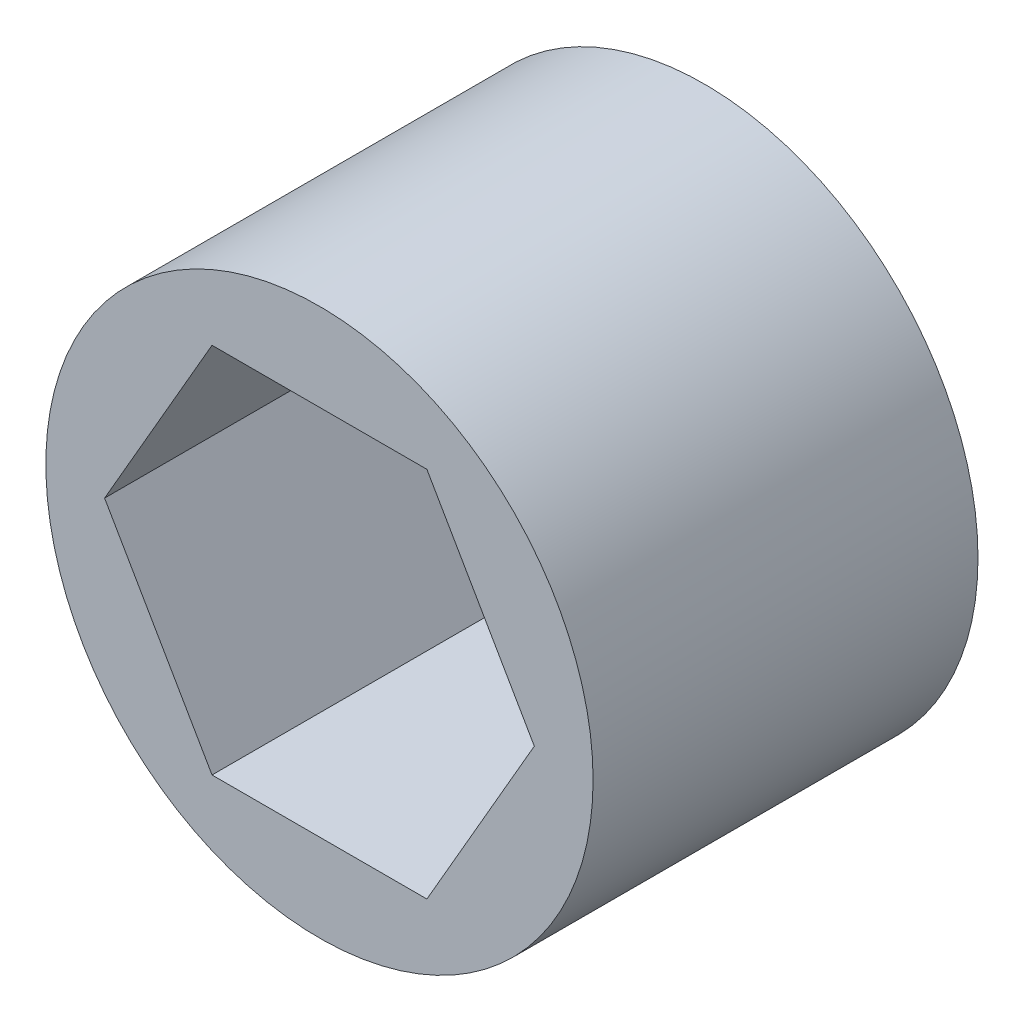
SolidWorks part; units mm, degrees
material "PET"
ref_plane "Front Plane" through (0, 0, 0) normal (0, 0, 1) x (1, 0, 0)
ref_plane "Top Plane" through (0, 0, 0) normal (0, 1, 0) x (1, 0, 0)
ref_plane "Right Plane" through (0, 0, 0) normal (1, 0, 0) x (0, 0, -1)
sketch "Sketch1" plane through (0, 0, 0) normal (0, 0, 1) x (1, 0, 0)
  line L7 (7.479, 0) -> (3.7395, 6.477)
  line L8 (3.7395, 6.477) -> (-3.7395, 6.477)
  line L9 (-3.7395, 6.477) -> (-7.479, 0)
  line L10 (-7.479, 0) -> (-3.7395, -6.477)
  line L11 (-3.7395, -6.477) -> (3.7395, -6.477)
  line L12 (3.7395, -6.477) -> (7.479, 0)
  circle A2 centre (0, 0) radius 6.477 construction
  circle A3 centre (0, 0) radius 9.525
  dimension "D1" = 19.05
  dimension "D2" = 12.954
extrude "Boss-Extrude1" add sketch "Sketch1" along normal mid plane 13.3985
equation "\"D1@Boss-Extrude1\"=0.655945-0.132500+(0.008110/2)"
